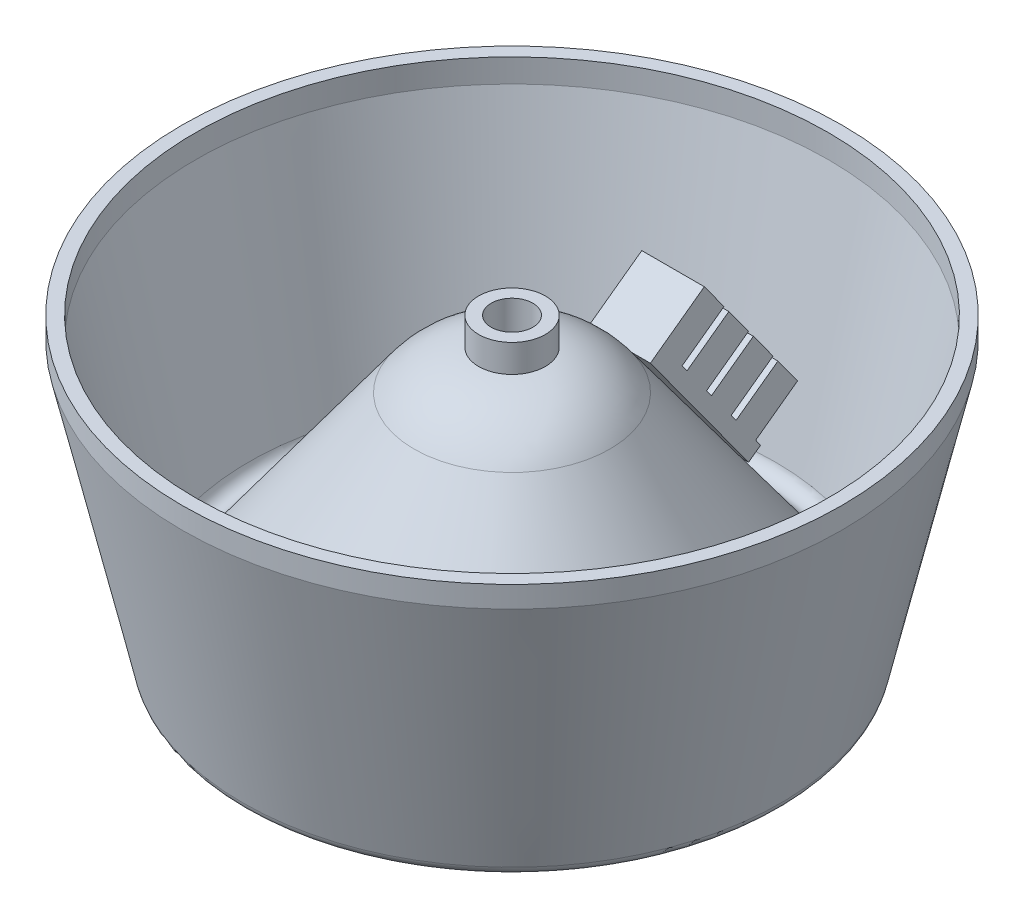
SolidWorks part; units mm, degrees
ref_plane "Front Plane" through (0, 0, 0) normal (0, 0, 1) x (1, 0, 0)
ref_plane "Top Plane" through (0, 0, 0) normal (0, 1, 0) x (1, 0, 0)
ref_plane "Right Plane" through (0, 0, 0) normal (1, 0, 0) x (0, 0, -1)
sketch "Sketch1" plane through (0, 0, 0) normal (1, 0, 0) x (0, 0, -1)
  line L5 (-80.2272, 37.7431) -> (80.2272, 37.7431) construction
  line L6 (-80.2272, 37.7431) -> (-80.2272, -37.7431) construction
  line L7 (-80.2272, -37.7431) -> (80.2272, -37.7431) construction
  line L8 (80.2272, 37.7431) -> (80.2272, -37.7431) construction
  line L9 (-80.2272, 37.7431) -> (80.2272, -37.7431) construction
  line L10 (-80.2272, -37.7431) -> (80.2272, 37.7431) construction
  line L16 (-59.1486, -32.4047) -> (-21.0684, 19.9267)
  line L19 (0, 0) -> (0, -37.7431) construction
  line L31 (-79.0589, 32.6139) -> (-64.4995, -31.3058)
  line L37 (-75.8668, 32.108) -> (-63.0406, -24.2023)
  line L38 (-57.6898, -25.3012) -> (-23.4941, 21.6919)
  line L39 (-8, 31.0864) -> (-8, 37.7431)
  line L40 (-8, 37.7431) -> (-5, 37.7431)
  line L42 (-5, 28.3387) -> (-5, 37.7431)
  line L44 (-77.3021, 38.4093) -> (-61.5744, -30.6396) construction
  line L45 (-61.5744, -30.6396) -> (-23.4941, 21.6919) construction
  line L46 (-79.0589, 32.6139) -> (-79.0589, 37.7431)
  line L47 (-79.0589, 37.7431) -> (-75.8668, 37.7431)
  line L48 (-75.8668, 37.7431) -> (-75.8668, 32.108)
  line L49 (-80.2272, 37.7431) -> (-64.4995, -31.3058) construction
  arc A7 (-59.1486, -32.4047) -> (-64.4995, -31.3058) centre (-61.5744, -30.6396) cw
  arc A9 (-23.4941, 21.6919) -> (-8, 31.0864) centre (-4.5333, 7.8946) cw
  arc A10 (-21.0684, 19.9267) -> (-5, 28.3387) centre (-4.5333, 7.8946) cw
  arc A11 (-57.6898, -25.3012) -> (-63.0406, -24.2023) centre (-60.1155, -23.5361) cw
  arc A12 (-61.5744, -30.6396) -> (-61.5744, -30.6396) centre (-61.5744, -30.6396) cw construction
  point P0 (0, 0)
  point P14 (17.18, -37.7431)
  point P29 (-63.0332, -37.7431)
  dimension "D1" = 3
  dimension "D3" = 3
  dimension "D2" = 3
revolve "Revolve7" add sketch "Sketch1" angle 360 about L19
ref_plane "Plane1" through (0, 18.6871, -25.6806) normal (0, 0.5884, -0.8086) x (-1, 0, 0)
sketch "Sketch2" plane through (0, 18.6871, -25.6806) normal (0, 0.5884, -0.8086) x (-1, 0, 0)
  line L0 (0, 0) -> (0, -58.519) construction
  line L1 (-7.5, 0) -> (7.5, 0)
  line L2 (7.5, 0) -> (7.5, -40)
  line L4 (-7.5, 0) -> (-7.5, -40)
  line L5 (-7.5, -40) -> (7.5, -40)
  point P3 (0, 0)
  point P6 (0, 0)
  point P9 (0, 0)
extrude "Boss-Extrude3" add sketch "Sketch2" along normal blind 1
sketch "Sketch3" plane through (0, 19.2755, -26.4892) normal (0, 0.5884, -0.8086) x (-1, 0, 0)
  line L0 (7.5, -40) -> (7.5, 0) construction
  line L1 (-7.5, 0) -> (7.5, 0)
  line L2 (-7.5, 0) -> (-7.5, -8)
  line L3 (-7.5, -8) -> (7.5, -8)
  line L4 (7.5, 0) -> (7.5, -8)
extrude "Boss-Extrude4" add sketch "Sketch3" along normal blind 15
ref_plane "Plane2" through (0, 19.2755, -26.4892) normal (0, -0.5884, 0.8086) x (1, 0, 0)
sketch "Sketch5" plane through (0, 19.2755, -26.4892) normal (0, -0.5884, 0.8086) x (1, 0, 0)
  line L0 (7.5, -8) -> (-7.5, -8) construction
  line L1 (0, -8) -> (0, 0) construction
  line L3 (-5.5, -7) -> (5.5, -7)
  line L4 (-5.5, -7) -> (-5.5, -1)
  line L5 (-5.5, -1) -> (5.5, -1)
  line L6 (5.5, -7) -> (5.5, -1)
  line L7 (-5.5, -7) -> (5.5, -1) construction
  line L8 (-5.5, -1) -> (5.5, -7) construction
  point P7 (0, -4)
extrude "Cut-Extrude1" cut sketch "Sketch5" against normal blind 13
sketch "Sketch6" plane through (0, -6.4687, -4.7071) normal (0, -0.8086, -0.5884) x (1, 0, 0)
  line L0 (-7.5, -47.7601) -> (-7.5, -32.7601) construction
  line L1 (7.5, -32.7601) -> (-7.5, -32.7601)
  line L2 (7.5, -32.7601) -> (7.5, -35.3441)
  line L3 (7.5, -35.3441) -> (-7.5, -35.3441)
  line L4 (-7.5, -32.7601) -> (-7.5, -35.3441)
extrude "Boss-Extrude5" add sketch "Sketch6" along normal blind 2
pattern_linear "LPattern1" count 4 spacing 10 along (0, -0.8086, -0.5884) of "Cut-Extrude1", "Boss-Extrude4", "Boss-Extrude5"
